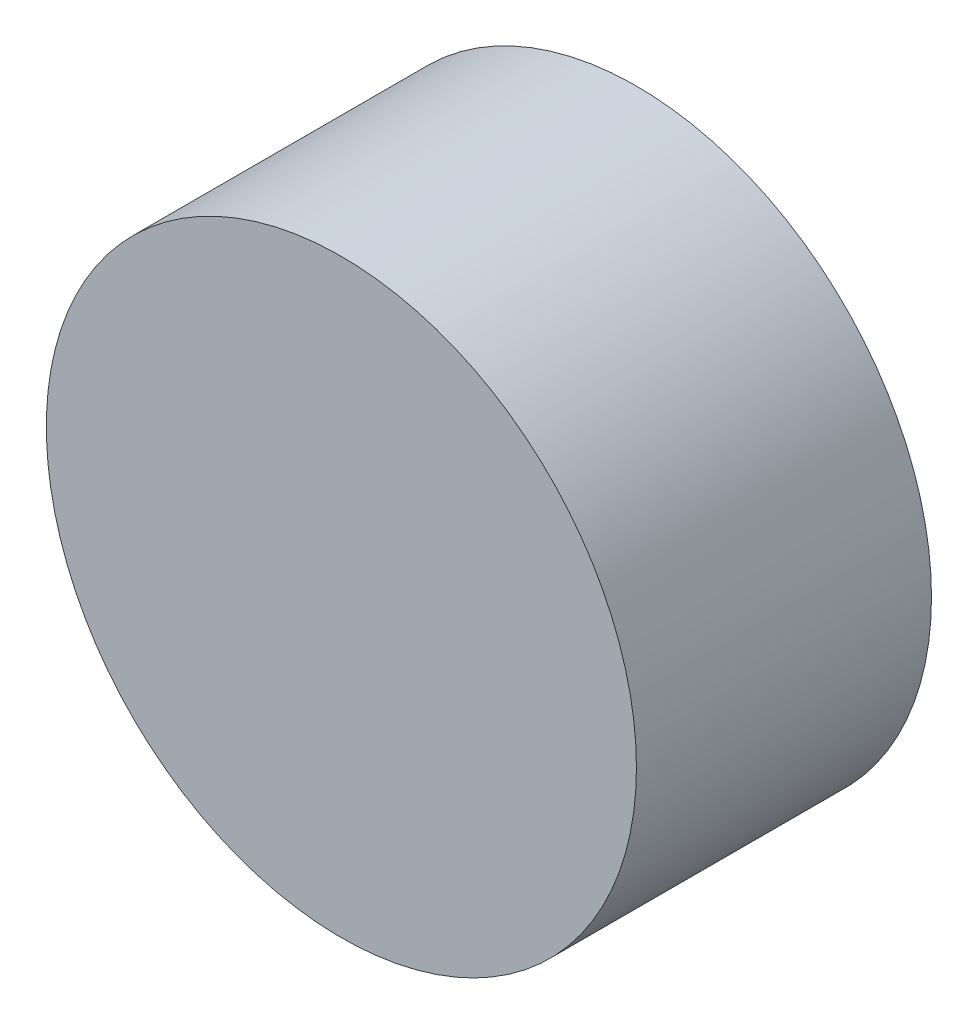
SolidWorks part; units mm, degrees
ref_plane "正面" through (0, 0, 0) normal (0, 0, 1) x (1, 0, 0)
ref_plane "平面" through (0, 0, 0) normal (0, 1, 0) x (1, 0, 0)
ref_plane "右側面" through (0, 0, 0) normal (1, 0, 0) x (0, 0, -1)
sketch "ｽｹｯﾁ1" plane through (0, 0, 0) normal (0, 0, 1) x (1, 0, 0)
  circle A0 centre (0, 0) radius 3
extrude "ﾎﾞｽ - 押し出し1" add sketch "ｽｹｯﾁ1" along normal blind 3
